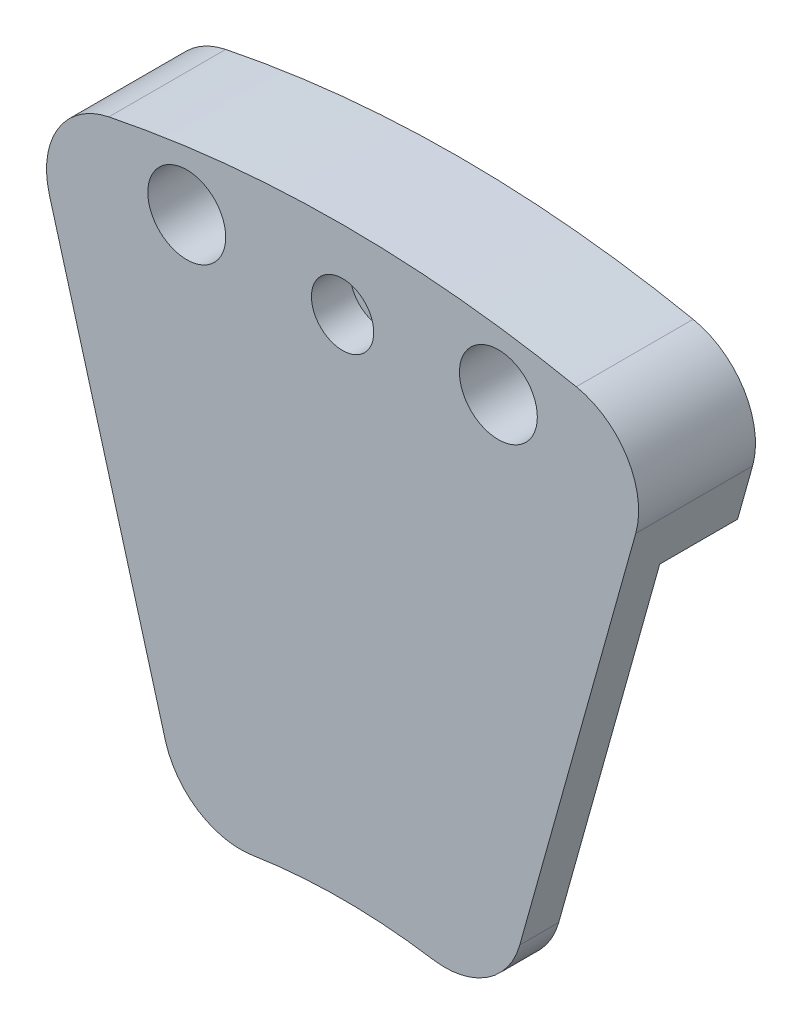
SolidWorks part; units mm, degrees
ref_plane "前视基准面" through (0, 0, 0) normal (0, 0, 1) x (1, 0, 0)
ref_plane "上视基准面" through (0, 0, 0) normal (0, 1, 0) x (1, 0, 0)
ref_plane "右视基准面" through (0, 0, 0) normal (1, 0, 0) x (0, 0, -1)
sketch "草图1" plane through (0, 0, 0) normal (0, 0, 1) x (1, 0, 0)
  line L2 (-37.6301, 134.4767) -> (-22.7463, 81.2872)
  line L3 (22.7463, 81.2872) -> (37.6301, 134.4767)
  line L4 (-37.6301, 134.4767) -> (-22.7463, 81.2872)
  line L5 (22.7463, 81.2872) -> (37.6301, 134.4767)
  arc A0 (0, 136) -> (0, 144) centre (0, 140) ccw construction
  arc A1 (0, 144) -> (0, 136) centre (0, 140) ccw construction
  arc A2 (0, 144) -> (0, 136) centre (0, 140) ccw
  arc A3 (0, 136) -> (0, 144) centre (0, 140) ccw
  arc A8 (-22.7463, 81.2872) -> (-13.1162, 73.9819) centre (-13.1162, 83.9819) ccw
  arc A9 (-13.1162, 73.9819) -> (-11.5731, 74.1017) centre (-13.1162, 83.9819) ccw
  arc A10 (11.5731, 74.1017) -> (-11.5731, 74.1017) centre (0, 0) ccw
  arc A11 (11.5731, 74.1017) -> (13.1162, 73.9819) centre (13.1162, 83.9819) ccw
  arc A12 (13.1162, 73.9819) -> (22.7463, 81.2872) centre (13.1162, 83.9819) ccw
  arc A13 (37.6301, 134.4767) -> (30, 146.9694) centre (28, 137.1714) ccw
  arc A14 (30, 146.9694) -> (-30, 146.9694) centre (0, 0) ccw
  arc A15 (-30, 146.9694) -> (-37.6301, 134.4767) centre (-28, 137.1714) ccw
  arc A16 (-22.7463, 81.2872) -> (-13.1162, 73.9819) centre (-13.1162, 83.9819) ccw
  arc A17 (-13.1162, 73.9819) -> (-11.5731, 74.1017) centre (-13.1162, 83.9819) ccw
  arc A18 (11.5731, 74.1017) -> (-11.5731, 74.1017) centre (0, 0) ccw
  arc A19 (11.5731, 74.1017) -> (13.1162, 73.9819) centre (13.1162, 83.9819) ccw
  arc A20 (13.1162, 73.9819) -> (22.7463, 81.2872) centre (13.1162, 83.9819) ccw
  arc A21 (37.6301, 134.4767) -> (30, 146.9694) centre (28, 137.1714) ccw
  arc A22 (30, 146.9694) -> (-30, 146.9694) centre (0, 0) ccw
  arc A23 (-30, 146.9694) -> (-37.6301, 134.4767) centre (-28, 137.1714) ccw
  dimension "D1" = 0
extrude "凸台-拉伸1" add sketch "草图1" along normal blind 5
sketch "草图2" plane through (0, 0, 0) normal (0, 0, -1) x (-1, 0, 0)
  line L0 (37.6301, 134.4767) -> (22.7463, 81.2872) construction
  line L1 (-22.7463, 81.2872) -> (-37.6301, 134.4767) construction
  line L2 (37.6301, 134.4767) -> (35.7054, 127.5985)
  line L3 (-35.7054, 127.5985) -> (-37.6301, 134.4767)
  arc A0 (-30, 146.9694) -> (-37.6301, 134.4767) centre (-28, 137.1714) ccw construction
  arc A1 (30, 146.9694) -> (-30, 146.9694) centre (0, 0) ccw construction
  arc A2 (37.6301, 134.4767) -> (30, 146.9694) centre (28, 137.1714) ccw construction
  arc A3 (-30, 146.9694) -> (-37.6301, 134.4767) centre (-28, 137.1714) ccw
  arc A4 (30, 146.9694) -> (-30, 146.9694) centre (0, 0) ccw
  arc A5 (37.6301, 134.4767) -> (30, 146.9694) centre (28, 137.1714) ccw
  arc A6 (35.7054, 127.5985) -> (-35.7054, 127.5985) centre (0, 0) ccw
  dimension "D1" = 132.5
extrude "凸台-拉伸2" add sketch "草图2" along normal blind 10
sketch "草图3" plane through (0, 0, 5) normal (0, 0, 1) x (1, 0, 0)
  circle A0 centre (-20, 141.0895) radius 2.15
  circle A1 centre (20, 141.0895) radius 2.15
extrude "切除-拉伸1" cut sketch "草图3" against normal blind 50
sketch "草图4" plane through (0, 0, 5) normal (0, 0, 1) x (1, 0, 0)
  circle A0 centre (-20, 141.0895) radius 5
  circle A1 centre (20, 141.0895) radius 5
  dimension "D1" = 10
  dimension "D2" = 10
extrude "切除-拉伸2" cut sketch "草图4" against normal blind 10
